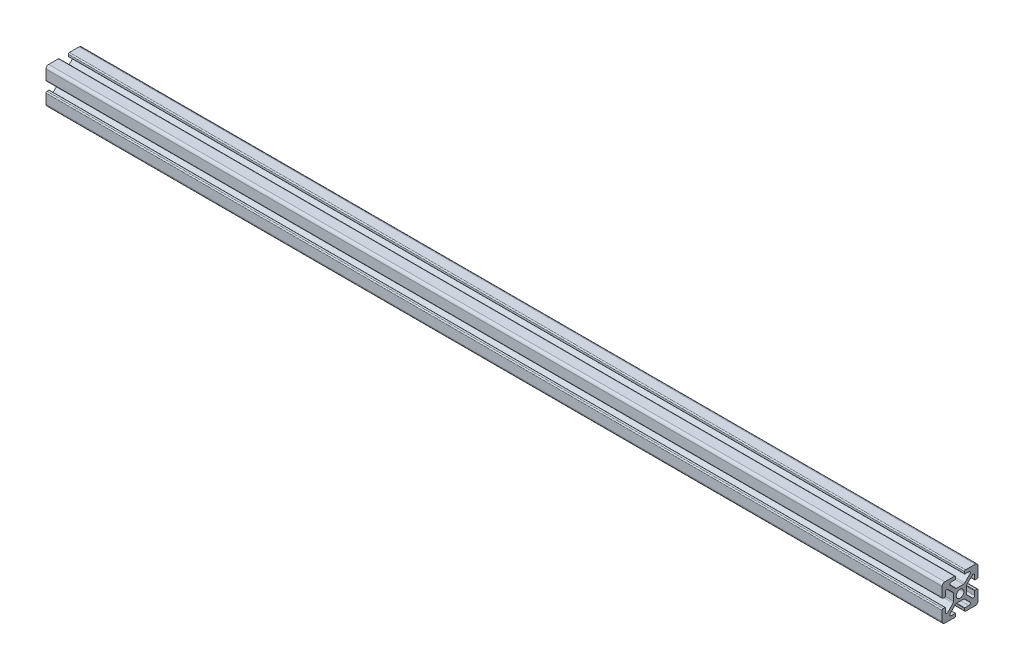
SolidWorks part; units mm, degrees
ref_plane "Front Plane" through (0, 0, 0) normal (0, 0, 1) x (1, 0, 0)
ref_plane "Top Plane" through (0, 0, 0) normal (0, 1, 0) x (1, 0, 0)
ref_plane "Right Plane" through (0, 0, 0) normal (1, 0, 0) x (0, 0, -1)
sketch "Sketch1" plane through (0, 0, 0) normal (1, 0, 0) x (0, 0, -1)
  line L0 (0, -10) -> (0, 10) construction
  line L1 (10, -10) -> (-10, -10)
  line L2 (10, -10) -> (10, 10)
  line L3 (10, 10) -> (0, 10)
  line L4 (-10, -10) -> (-10, 10)
  line L5 (10, -10) -> (-10, 10) construction
  line L6 (10, 10) -> (-10, -10) construction
  line L7 (10, 0) -> (-10, 0) construction
  line L8 (-2.5, 9.4) -> (-2.5, 8.3731)
  line L9 (-2.7, 8.1731) -> (-4.95, 8.1731)
  line L10 (-5.5157, 6.8075) -> (-2.6011, 3.8929)
  line L11 (-1.894, 3.6) -> (0, 3.6)
  line L12 (-5.3502, 4.0584) -> (-4.0584, 5.3502) construction
  line L13 (-3.825, 8.1731) -> (-3.825, 10) construction
  line L14 (-3.1, 10) -> (-10, 10)
  line L15 (-5.75, 7.3731) -> (5.75, 7.3731) construction
  circle A0 centre (0, 0) radius 2.15
  arc A1 (-4.95, 8.1731) -> (-5.5157, 6.8075) centre (-4.95, 7.3731) ccw
  arc A2 (-2.6011, 3.8929) -> (-1.894, 3.6) centre (-1.894, 4.6) ccw
  arc A3 (-2.5, 8.3731) -> (-2.7, 8.1731) centre (-2.7, 8.3731) cw
  arc A4 (-2.5, 9.4) -> (-3.1, 10) centre (-3.1, 9.4) ccw
  point P0 (0, 0)
  point P9 (0, 0)
  point P12 (0, 0)
  point P22 (-4.7043, 4.7043)
  point P32 (-2.5, 10)
  point P33 (-2.5, 8.8866)
  point P35 (-4.0584, 5.3502)
  point P37 (0, 7.3731)
  dimension "Center Hole Diameter" = 4.3
  dimension "D4" = 1
  dimension "D5" = 0.2
  dimension "D6" = 0.6
  dimension "D3" = 0.8
  dimension "Rail Height" = 20
  dimension "D7" = 6.4
  dimension "T Slot Width" = 5
  dimension "D10" = 10
  dimension "Rail Width" = 20
  dimension "D2" = 11.5
sketch "Sketch2" plane through (0, 0, 0) normal (0, 0, 1) x (1, 0, 0)
  line L0 (-132.4, 10) -> (-132.4, -10) construction
  line L1 (152.4, -10) -> (-152.4, -10) construction
  line L2 (152.4, -10) -> (152.4, 10) construction
  line L3 (152.4, 10) -> (-152.4, 10) construction
  line L4 (-152.4, -10) -> (-152.4, 10) construction
  line L5 (152.4, -10) -> (-152.4, 10) construction
  line L6 (152.4, 10) -> (-152.4, -10) construction
  line L7 (132.4, 10) -> (132.4, -10) construction
  point P0 (0, 0)
  point P12 (132.4, 0)
  dimension "Length" = 304.8
  dimension "D1" = 20
  dimension "D2" = 20
sketch "Sketch3" plane through (0, 0, 0) normal (1, 0, 0) x (0, 0, -1)
  line L0 (-5.5157, 6.8075) -> (-2.6011, 3.8929) construction
  line L5 (-3.1, 10) -> (-10, 10) construction
  line L6 (-2.5, 9.4) -> (-2.5, 8.3731) construction
  line L7 (-2.7, 8.1731) -> (-4.95, 8.1731) construction
  line L8 (-1.894, 3.6) -> (0, 3.6) construction
  line L9 (-5.5157, 6.8075) -> (-2.6011, 3.8929)
  line L10 (-10, 10) -> (0, 0) construction
  line L12 (-3.6, 1.894) -> (-3.6, 0)
  line L13 (-8.1731, 2.7) -> (-8.1731, 4.95)
  line L14 (-3.1, 10) -> (-8.5, 10)
  line L15 (-2.5, 9.4) -> (-2.5, 8.3731)
  line L16 (-2.7, 8.1731) -> (-4.95, 8.1731)
  line L17 (-1.894, 3.6) -> (0, 3.6)
  line L18 (-9.4, 2.5) -> (-8.3731, 2.5)
  line L19 (-10, 3.1) -> (-10, 8.5)
  line L20 (-6.8075, 5.5157) -> (-3.8929, 2.6011)
  line L21 (-3.6, 0) -> (-2.15, 0)
  line L22 (0, 3.6) -> (0, 2.15)
  arc A0 (-2.5, 9.4) -> (-3.1, 10) centre (-3.1, 9.4) ccw construction
  arc A1 (-2.7, 8.1731) -> (-2.5, 8.3731) centre (-2.7, 8.3731) ccw construction
  arc A2 (-4.95, 8.1731) -> (-5.5157, 6.8075) centre (-4.95, 7.3731) ccw construction
  arc A3 (-2.6011, 3.8929) -> (-1.894, 3.6) centre (-1.894, 4.6) ccw construction
  arc A4 (-2.5, 9.4) -> (-3.1, 10) centre (-3.1, 9.4) ccw
  arc A5 (-2.7, 8.1731) -> (-2.5, 8.3731) centre (-2.7, 8.3731) ccw
  arc A6 (-4.95, 8.1731) -> (-5.5157, 6.8075) centre (-4.95, 7.3731) ccw
  arc A7 (-2.6011, 3.8929) -> (-1.894, 3.6) centre (-1.894, 4.6) ccw
  arc A8 (-3.8929, 2.6011) -> (-3.6, 1.894) centre (-4.6, 1.894) cw
  arc A9 (-8.1731, 4.95) -> (-6.8075, 5.5157) centre (-7.3731, 4.95) cw
  arc A10 (-8.1731, 2.7) -> (-8.3731, 2.5) centre (-8.3731, 2.7) cw
  arc A11 (-9.4, 2.5) -> (-10, 3.1) centre (-9.4, 3.1) cw
  circle A12 centre (0, 0) radius 2.15 construction
  arc A13 (0, 2.15) -> (-2.15, 0) centre (0, 0) ccw
  arc A14 (-10, 8.5) -> (-8.5, 10) centre (-8.5, 8.5) cw
  dimension "D1" = 1.5
extrude "Boss-Extrude1" add sketch "Sketch3" against normal up to vertex (152.4 mm away) and the other way up to vertex (152.4 mm away) up to point (-152.4, 10, 0) other way up to point (152.4, 10, 0)
mirror "Mirror1" about plane through (0, 0, 0) normal (0, 1, 0) of bodies 104
mirror "Mirror2" about plane through (0, 0, 0) normal (0, 0, 1) of bodies 105
sketch "Sketch4" plane through (152.4, 0, 0) normal (1, 0, 0) x (0, 0, -1)
  line L36 (1.894, 3.6) -> (-1.894, 3.6)
  line L37 (-2.6011, 3.8929) -> (-5.5157, 6.8075)
  line L38 (-4.95, 8.1731) -> (-2.7, 8.1731)
  line L39 (-2.5, 8.3731) -> (-2.5, 9.4)
  line L40 (-3.1, 10) -> (-8.5, 10)
  line L41 (-10, 8.5) -> (-10, 3.1)
  line L42 (-9.4, 2.5) -> (-8.3731, 2.5)
  line L43 (-8.1731, 2.7) -> (-8.1731, 4.95)
  line L44 (-6.8075, 5.5157) -> (-3.8929, 2.6011)
  line L45 (-3.6, 1.894) -> (-3.6, -1.894)
  line L46 (-3.8929, -2.6011) -> (-6.8075, -5.5157)
  line L47 (-8.1731, -4.95) -> (-8.1731, -2.7)
  line L48 (-8.3731, -2.5) -> (-9.4, -2.5)
  line L49 (-10, -3.1) -> (-10, -8.5)
  line L50 (-8.5, -10) -> (-3.1, -10)
  line L51 (-2.5, -9.4) -> (-2.5, -8.3731)
  line L52 (-2.7, -8.1731) -> (-4.95, -8.1731)
  line L53 (-5.5157, -6.8075) -> (-2.6011, -3.8929)
  line L54 (-1.894, -3.6) -> (1.894, -3.6)
  line L55 (2.6011, -3.8929) -> (5.5157, -6.8075)
  line L56 (4.95, -8.1731) -> (2.7, -8.1731)
  line L57 (2.5, -8.3731) -> (2.5, -9.4)
  line L58 (3.1, -10) -> (8.5, -10)
  line L59 (10, -8.5) -> (10, -3.1)
  line L60 (9.4, -2.5) -> (8.3731, -2.5)
  line L61 (8.1731, -2.7) -> (8.1731, -4.95)
  line L62 (6.8075, -5.5157) -> (3.8929, -2.6011)
  line L63 (3.6, -1.894) -> (3.6, 1.894)
  line L64 (3.8929, 2.6011) -> (6.8075, 5.5157)
  line L65 (8.1731, 4.95) -> (8.1731, 2.7)
  line L66 (8.3731, 2.5) -> (9.4, 2.5)
  line L67 (10, 3.1) -> (10, 8.5)
  line L68 (8.5, 10) -> (3.1, 10)
  line L69 (2.5, 9.4) -> (2.5, 8.3731)
  line L70 (2.7, 8.1731) -> (4.95, 8.1731)
  line L71 (5.5157, 6.8075) -> (2.6011, 3.8929)
  line L72 (1.894, 3.6) -> (-1.894, 3.6)
  line L73 (-2.6011, 3.8929) -> (-5.5157, 6.8075)
  line L74 (-4.95, 8.1731) -> (-2.7, 8.1731)
  line L75 (-2.5, 8.3731) -> (-2.5, 9.4)
  line L76 (-3.1, 10) -> (-8.5, 10)
  line L77 (-10, 8.5) -> (-10, 3.1)
  line L78 (-9.4, 2.5) -> (-8.3731, 2.5)
  line L79 (-8.1731, 2.7) -> (-8.1731, 4.95)
  line L80 (-6.8075, 5.5157) -> (-3.8929, 2.6011)
  line L81 (-3.6, 1.894) -> (-3.6, -1.894)
  line L82 (-3.8929, -2.6011) -> (-6.8075, -5.5157)
  line L83 (-8.1731, -4.95) -> (-8.1731, -2.7)
  line L84 (-8.3731, -2.5) -> (-9.4, -2.5)
  line L85 (-10, -3.1) -> (-10, -8.5)
  line L86 (-8.5, -10) -> (-3.1, -10)
  line L87 (-2.5, -9.4) -> (-2.5, -8.3731)
  line L88 (-2.7, -8.1731) -> (-4.95, -8.1731)
  line L89 (-5.5157, -6.8075) -> (-2.6011, -3.8929)
  line L90 (-1.894, -3.6) -> (1.894, -3.6)
  line L91 (2.6011, -3.8929) -> (5.5157, -6.8075)
  line L92 (4.95, -8.1731) -> (2.7, -8.1731)
  line L93 (2.5, -8.3731) -> (2.5, -9.4)
  line L94 (3.1, -10) -> (8.5, -10)
  line L95 (10, -8.5) -> (10, -3.1)
  line L96 (9.4, -2.5) -> (8.3731, -2.5)
  line L97 (8.1731, -2.7) -> (8.1731, -4.95)
  line L98 (6.8075, -5.5157) -> (3.8929, -2.6011)
  line L99 (3.6, -1.894) -> (3.6, 1.894)
  line L100 (3.8929, 2.6011) -> (6.8075, 5.5157)
  line L101 (8.1731, 4.95) -> (8.1731, 2.7)
  line L102 (8.3731, 2.5) -> (9.4, 2.5)
  line L103 (10, 3.1) -> (10, 8.5)
  line L104 (8.5, 10) -> (3.1, 10)
  line L105 (2.5, 9.4) -> (2.5, 8.3731)
  line L106 (2.7, 8.1731) -> (4.95, 8.1731)
  line L107 (5.5157, 6.8075) -> (2.6011, 3.8929)
  circle A0 centre (0, 0) radius 2.15 construction
  circle A1 centre (0, 0) radius 2.15
  arc A36 (1.894, 3.6) -> (2.6011, 3.8929) centre (1.894, 4.6) ccw
  arc A37 (-2.6011, 3.8929) -> (-1.894, 3.6) centre (-1.894, 4.6) ccw
  arc A38 (-4.95, 8.1731) -> (-5.5157, 6.8075) centre (-4.95, 7.3731) ccw
  arc A39 (-2.7, 8.1731) -> (-2.5, 8.3731) centre (-2.7, 8.3731) ccw
  arc A40 (-2.5, 9.4) -> (-3.1, 10) centre (-3.1, 9.4) ccw
  arc A41 (-8.5, 10) -> (-10, 8.5) centre (-8.5, 8.5) ccw
  arc A42 (-10, 3.1) -> (-9.4, 2.5) centre (-9.4, 3.1) ccw
  arc A43 (-8.3731, 2.5) -> (-8.1731, 2.7) centre (-8.3731, 2.7) ccw
  arc A44 (-6.8075, 5.5157) -> (-8.1731, 4.95) centre (-7.3731, 4.95) ccw
  arc A45 (-3.6, 1.894) -> (-3.8929, 2.6011) centre (-4.6, 1.894) ccw
  arc A46 (-3.8929, -2.6011) -> (-3.6, -1.894) centre (-4.6, -1.894) ccw
  arc A47 (-8.1731, -4.95) -> (-6.8075, -5.5157) centre (-7.3731, -4.95) ccw
  arc A48 (-8.1731, -2.7) -> (-8.3731, -2.5) centre (-8.3731, -2.7) ccw
  arc A49 (-9.4, -2.5) -> (-10, -3.1) centre (-9.4, -3.1) ccw
  arc A50 (-10, -8.5) -> (-8.5, -10) centre (-8.5, -8.5) ccw
  arc A51 (-3.1, -10) -> (-2.5, -9.4) centre (-3.1, -9.4) ccw
  arc A52 (-2.5, -8.3731) -> (-2.7, -8.1731) centre (-2.7, -8.3731) ccw
  arc A53 (-5.5157, -6.8075) -> (-4.95, -8.1731) centre (-4.95, -7.3731) ccw
  arc A54 (-1.894, -3.6) -> (-2.6011, -3.8929) centre (-1.894, -4.6) ccw
  arc A55 (2.6011, -3.8929) -> (1.894, -3.6) centre (1.894, -4.6) ccw
  arc A56 (4.95, -8.1731) -> (5.5157, -6.8075) centre (4.95, -7.3731) ccw
  arc A57 (2.7, -8.1731) -> (2.5, -8.3731) centre (2.7, -8.3731) ccw
  arc A58 (2.5, -9.4) -> (3.1, -10) centre (3.1, -9.4) ccw
  arc A59 (8.5, -10) -> (10, -8.5) centre (8.5, -8.5) ccw
  arc A60 (10, -3.1) -> (9.4, -2.5) centre (9.4, -3.1) ccw
  arc A61 (8.3731, -2.5) -> (8.1731, -2.7) centre (8.3731, -2.7) ccw
  arc A62 (6.8075, -5.5157) -> (8.1731, -4.95) centre (7.3731, -4.95) ccw
  arc A63 (3.6, -1.894) -> (3.8929, -2.6011) centre (4.6, -1.894) ccw
  arc A64 (3.8929, 2.6011) -> (3.6, 1.894) centre (4.6, 1.894) ccw
  arc A65 (8.1731, 4.95) -> (6.8075, 5.5157) centre (7.3731, 4.95) ccw
  arc A66 (8.1731, 2.7) -> (8.3731, 2.5) centre (8.3731, 2.7) ccw
  arc A67 (9.4, 2.5) -> (10, 3.1) centre (9.4, 3.1) ccw
  arc A68 (10, 8.5) -> (8.5, 10) centre (8.5, 8.5) ccw
  arc A69 (3.1, 10) -> (2.5, 9.4) centre (3.1, 9.4) ccw
  arc A70 (2.5, 8.3731) -> (2.7, 8.1731) centre (2.7, 8.3731) ccw
  arc A71 (5.5157, 6.8075) -> (4.95, 8.1731) centre (4.95, 7.3731) ccw
  arc A72 (1.894, 3.6) -> (2.6011, 3.8929) centre (1.894, 4.6) ccw
  arc A73 (-2.6011, 3.8929) -> (-1.894, 3.6) centre (-1.894, 4.6) ccw
  arc A74 (-4.95, 8.1731) -> (-5.5157, 6.8075) centre (-4.95, 7.3731) ccw
  arc A75 (-2.7, 8.1731) -> (-2.5, 8.3731) centre (-2.7, 8.3731) ccw
  arc A76 (-2.5, 9.4) -> (-3.1, 10) centre (-3.1, 9.4) ccw
  arc A77 (-8.5, 10) -> (-10, 8.5) centre (-8.5, 8.5) ccw
  arc A78 (-10, 3.1) -> (-9.4, 2.5) centre (-9.4, 3.1) ccw
  arc A79 (-8.3731, 2.5) -> (-8.1731, 2.7) centre (-8.3731, 2.7) ccw
  arc A80 (-6.8075, 5.5157) -> (-8.1731, 4.95) centre (-7.3731, 4.95) ccw
  arc A81 (-3.6, 1.894) -> (-3.8929, 2.6011) centre (-4.6, 1.894) ccw
  arc A82 (-3.8929, -2.6011) -> (-3.6, -1.894) centre (-4.6, -1.894) ccw
  arc A83 (-8.1731, -4.95) -> (-6.8075, -5.5157) centre (-7.3731, -4.95) ccw
  arc A84 (-8.1731, -2.7) -> (-8.3731, -2.5) centre (-8.3731, -2.7) ccw
  arc A85 (-9.4, -2.5) -> (-10, -3.1) centre (-9.4, -3.1) ccw
  arc A86 (-10, -8.5) -> (-8.5, -10) centre (-8.5, -8.5) ccw
  arc A87 (-3.1, -10) -> (-2.5, -9.4) centre (-3.1, -9.4) ccw
  arc A88 (-2.5, -8.3731) -> (-2.7, -8.1731) centre (-2.7, -8.3731) ccw
  arc A89 (-5.5157, -6.8075) -> (-4.95, -8.1731) centre (-4.95, -7.3731) ccw
  arc A90 (-1.894, -3.6) -> (-2.6011, -3.8929) centre (-1.894, -4.6) ccw
  arc A91 (2.6011, -3.8929) -> (1.894, -3.6) centre (1.894, -4.6) ccw
  arc A92 (4.95, -8.1731) -> (5.5157, -6.8075) centre (4.95, -7.3731) ccw
  arc A93 (2.7, -8.1731) -> (2.5, -8.3731) centre (2.7, -8.3731) ccw
  arc A94 (2.5, -9.4) -> (3.1, -10) centre (3.1, -9.4) ccw
  arc A95 (8.5, -10) -> (10, -8.5) centre (8.5, -8.5) ccw
  arc A96 (10, -3.1) -> (9.4, -2.5) centre (9.4, -3.1) ccw
  arc A97 (8.3731, -2.5) -> (8.1731, -2.7) centre (8.3731, -2.7) ccw
  arc A98 (6.8075, -5.5157) -> (8.1731, -4.95) centre (7.3731, -4.95) ccw
  arc A99 (3.6, -1.894) -> (3.8929, -2.6011) centre (4.6, -1.894) ccw
  arc A100 (3.8929, 2.6011) -> (3.6, 1.894) centre (4.6, 1.894) ccw
  arc A101 (8.1731, 4.95) -> (6.8075, 5.5157) centre (7.3731, 4.95) ccw
  arc A102 (8.1731, 2.7) -> (8.3731, 2.5) centre (8.3731, 2.7) ccw
  arc A103 (9.4, 2.5) -> (10, 3.1) centre (9.4, 3.1) ccw
  arc A104 (10, 8.5) -> (8.5, 10) centre (8.5, 8.5) ccw
  arc A105 (3.1, 10) -> (2.5, 9.4) centre (3.1, 9.4) ccw
  arc A106 (2.5, 8.3731) -> (2.7, 8.1731) centre (2.7, 8.3731) ccw
  arc A107 (5.5157, 6.8075) -> (4.95, 8.1731) centre (4.95, 7.3731) ccw
  dimension "D1" = 0
extrude "Boss-Extrude2" add sketch "Sketch4" along normal offset from surface (195.2 mm away) 500 up to face at (-152.4, 0, 0)
equation "\"D10@Sketch1\" = \"Rail Height@Sketch1\" / 2"
equation "\"D2@Sketch2\"=\"D1@Sketch2\""
